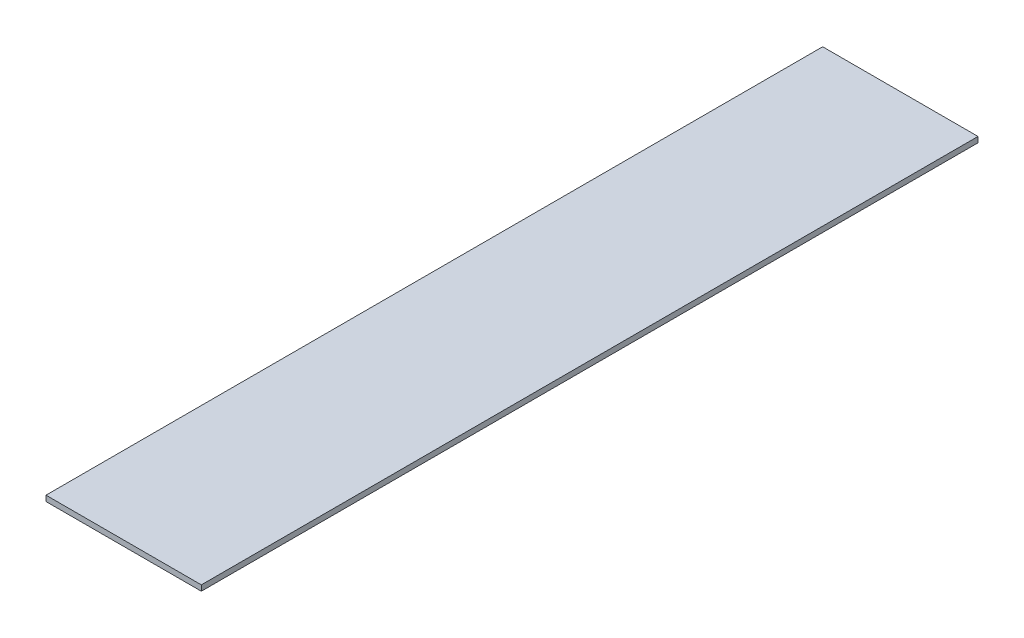
SolidWorks part; units mm, degrees
material "Maple"
ref_plane "Front Plane" through (0, 0, 0) normal (0, 0, 1) x (1, 0, 0)
ref_plane "Top Plane" through (0, 0, 0) normal (0, 1, 0) x (1, 0, 0)
ref_plane "Right Plane" through (0, 0, 0) normal (1, 0, 0) x (0, 0, -1)
sketch "Sketch1" plane through (0, 0, 0) normal (0, 1, 0) x (1, 0, 0)
  line L1 (0, 0) -> (355.6, 0)
  line L2 (0, 0) -> (0, 1778)
  line L3 (0, 1778) -> (355.6, 1778)
  line L4 (355.6, 0) -> (355.6, 1778)
  dimension "D1" = 355.6
  dimension "D2" = 1778
extrude "Boss-Extrude1" add sketch "Sketch1" along normal blind 12.7
